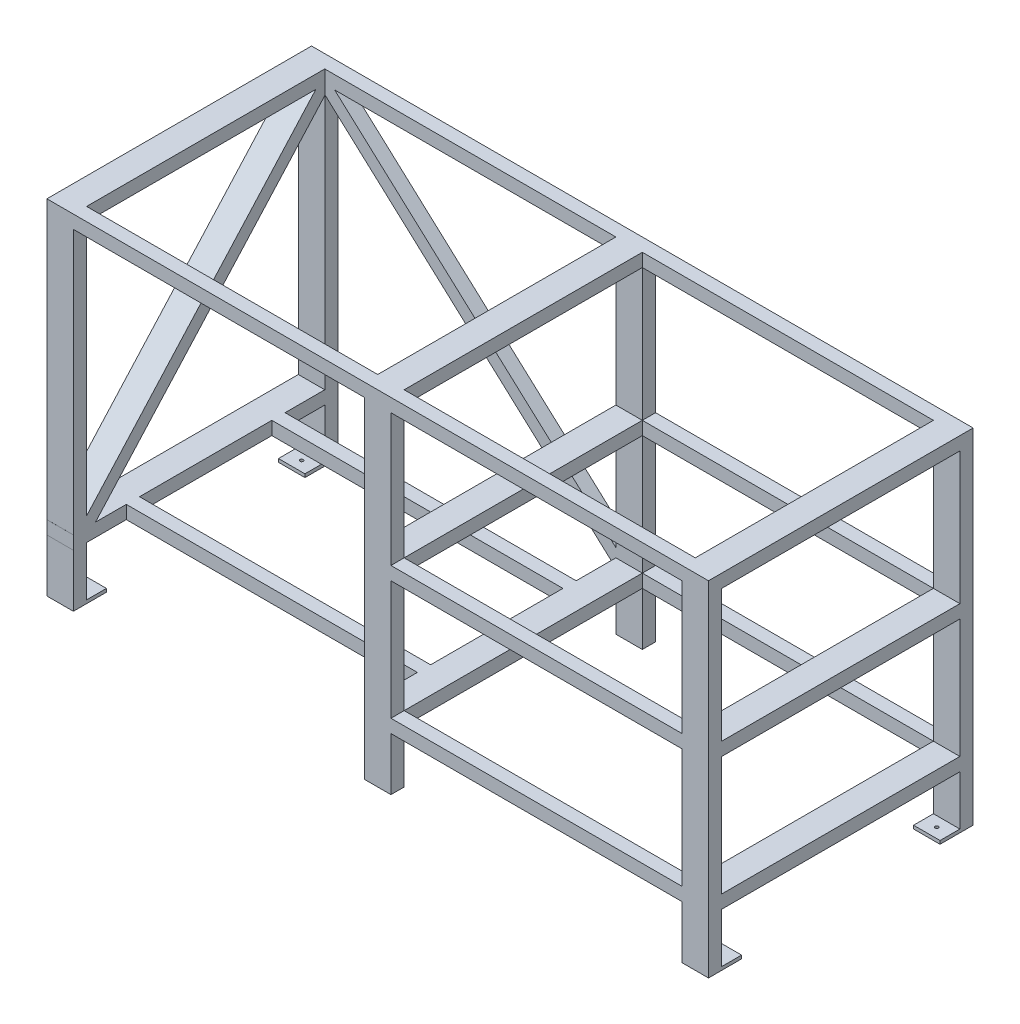
SolidWorks part; units mm, degrees
ref_plane "Front Plane" through (0, 0, 0) normal (0, 0, 1) x (1, 0, 0)
ref_plane "Top Plane" through (0, 0, 0) normal (0, 1, 0) x (1, 0, 0)
ref_plane "Right Plane" through (0, 0, 0) normal (1, 0, 0) x (0, 0, -1)
sketch "Sketch1" plane through (0, 0, 0) normal (0, 1, 0) x (1, 0, 0)
  line L0 (0, 0) -> (0, -232.9412) construction
  line L1 (-396.4706, 0) -> (-900, 0) construction
  line L2 (0, 360) -> (0, 400) construction
  line L3 (-1000, -360) -> (-920, -360)
  line L4 (-1000, -360) -> (-1000, -400)
  line L5 (-1000, -400) -> (-920, -400)
  line L6 (-920, -360) -> (-920, -400)
  line L7 (40, -360) -> (-40, -360)
  line L8 (0, -360) -> (0, -400) construction
  line L9 (40, -400) -> (-40, -400)
  line L10 (-40, -360) -> (-40, -400)
  line L11 (-40, 360) -> (-40, 400)
  line L12 (40, 400) -> (-40, 400)
  line L13 (40, 360) -> (-40, 360)
  line L14 (-920, 360) -> (-920, 400)
  line L15 (-1000, 400) -> (-920, 400)
  line L16 (-1000, 360) -> (-1000, 400)
  line L17 (-1000, 360) -> (-920, 360)
  line L18 (40, -360) -> (40, -400)
  line L19 (40, 360) -> (40, 400)
  line L20 (920, -360) -> (920, -400)
  line L21 (1000, -400) -> (920, -400)
  line L22 (1000, -360) -> (1000, -400)
  line L23 (1000, -360) -> (920, -360)
  line L24 (1000, 360) -> (920, 360)
  line L25 (1000, 360) -> (1000, 400)
  line L26 (1000, 400) -> (920, 400)
  line L27 (920, 360) -> (920, 400)
  dimension "D1" = 40
  dimension "D2" = 80
  dimension "D3" = 40
  dimension "D4" = 40
  dimension "D5" = 0
  dimension "D6" = 400
  dimension "D7" = 1000
  dimension "D8" = 0
  dimension "D9" = 400
extrude "Boss-Extrude1" add sketch "Sketch1" along normal blind 1000
ref_plane "Plane1" through (0, 200, 0) normal (0, -1, 0) x (-1, 0, 0)
sketch "Sketch3" plane through (0, 200, 0) normal (0, -1, 0) x (-1, 0, 0)
  line L0 (920, -240) -> (40, -240)
  line L1 (1000, 400) -> (920, 400)
  line L2 (1000, 400) -> (1000, -400.0751)
  line L3 (40, -400) -> (-1000, -400)
  line L4 (-1000, 400) -> (-1000, -400)
  line L5 (1000, -400) -> (920, -400) construction
  line L6 (920, 400) -> (920, 240)
  line L7 (40, 400) -> (-1000, 400)
  line L8 (40, 400) -> (40, 240)
  line L9 (-40, 360) -> (-920, 360)
  line L10 (-40, 360) -> (-40, -360)
  line L11 (-40, -360) -> (-920, -360)
  line L12 (-920, 360) -> (-920, -360)
  line L13 (920, -200) -> (40, -200)
  line L14 (920, 240) -> (40, 240)
  line L15 (920, 200) -> (40, 200)
  line L16 (1000, -400.0751) -> (920, -400.0751)
  line L17 (40, 200) -> (40, -200)
  line L18 (40, -240) -> (40, -400)
  line L19 (920, -240) -> (920, -400.0751)
  line L20 (920, 200) -> (920, -200)
  dimension "D1" = 200
  dimension "D2" = 40
  dimension "D3" = 200
  dimension "D4" = 40
extrude "Boss-Extrude2" add sketch "Sketch3" along normal blind 40
ref_plane "Plane3" through (0, 600, 0) normal (0, -1, 0) x (-1, 0, 0)
sketch "Sketch4" plane through (0, 600, 0) normal (0, -1, 0) x (-1, 0, 0)
  line L1 (40, 400) -> (-1000, 400)
  line L2 (40, 400) -> (40, -400)
  line L3 (40, -400) -> (-1000, -400)
  line L4 (-1000, 400) -> (-1000, -400)
  line L5 (-40, 360) -> (-920, 360)
  line L6 (-40, 360) -> (-40, -360)
  line L7 (-40, -360) -> (-920, -360)
  line L8 (-920, 360) -> (-920, -360)
extrude "Boss-Extrude4" add sketch "Sketch4" along normal blind 40
sketch "Sketch6" plane through (0, 1000, 0) normal (0, 1, 0) x (1, 0, 0)
  line L0 (40, -360) -> (-40, -360) construction
  line L1 (-1000, 400) -> (1000, 400)
  line L2 (-1000, 400) -> (-1000, -400)
  line L3 (-1000, -400) -> (1000, -400)
  line L4 (1000, 400) -> (1000, -400)
  line L5 (-920, 360) -> (-40, 360)
  line L6 (-920, 360) -> (-920, -360)
  line L7 (-920, -360) -> (-40, -360)
  line L8 (-40, 360) -> (-40, -360)
  line L10 (40, 360) -> (920, 360)
  line L11 (40, 360) -> (40, -360)
  line L12 (40, -360) -> (920, -360)
  line L13 (920, 360) -> (920, -360)
extrude "Boss-Extrude5" add sketch "Sketch6" along normal blind 40
sketch3d "3DSketch1"
  line L0 (-920, 200, 360) -> (-1000, 200, 360) construction
  line L1 (-960, 200, 360) -> (-960, 1000, -360)
  line L2 (-1000, 1000, -360) -> (-920, 1000, -360) construction
ref_plane "Plane4" through (-960, 200, 360) normal (0, 0.7433, -0.669) x (1, 0, 0)
sketch "Sketch7" plane through (-960, 200, 360) normal (0, 0.7433, -0.669) x (1, 0, 0)
  line L1 (-40, -20) -> (40, -20)
  line L2 (-40, -20) -> (-40, 20)
  line L3 (-40, 20) -> (40, 20)
  line L4 (40, -20) -> (40, 20)
  dimension "D1" = 20
  dimension "D2" = 40
  dimension "D3" = 40
  dimension "D4" = 80
sweep "Sweep1" add profiles "Sketch7" path "3DSketch1"
sketch3d "3DSketch2"
  line L0 (-40, 200, -380) -> (-920, 1000, -380)
  line L2 (-920, 1000, -360) -> (-920, 1000, -400) construction
ref_plane "Plane5" through (-40, 200, -380) normal (-0.7399, 0.6727, 0) x (0, 0, 1)
sketch "Sketch8" plane through (-40, 200, -380) normal (-0.7399, 0.6727, 0) x (0, 0, 1)
  line L1 (-20, 20) -> (20, 20)
  line L2 (-20, 20) -> (-20, -20)
  line L3 (-20, -20) -> (20, -20)
  line L4 (20, 20) -> (20, -20)
  dimension "D1" = 20
  dimension "D2" = 40
  dimension "D3" = 20
  dimension "D4" = 40
sweep "Sweep2" add profiles "Sketch8" path "3DSketch2"
sketch "Sketch9" plane through (0, 0, 0) normal (0, -1, 0) x (1, 0, 0)
  line L0 (1000, -400) -> (920, -400) construction
  line L1 (1000, -360) -> (920, -360)
  line L2 (1000, -360) -> (1000, -300)
  line L3 (1000, -300) -> (920, -300)
  line L4 (920, -360) -> (920, -300)
  circle A0 centre (960, -330) radius 5
  dimension "D2" = 10
  dimension "D1" = 100
  dimension "D3" = 40
  dimension "D4" = 30
extrude "Boss-Extrude6" add sketch "Sketch9" against normal blind 10 contours L2 L3 L4 L1
hole_wizard "Ø10.0 (10) Diameter Hole1" positions "Sketch11" profile "Sketch10" hole size "Ø10.0" standard "ANSI Metric"
sketch "Sketch11" plane through (0, 10, 0) normal (0, 1, 0) x (1, 0, 0)
  line L0 (1000, 300) -> (920, 300) construction
  point P0 (960, 330)
  dimension "D1" = 30
sketch "Sketch10" plane through (960, 10, -330) normal (1, 0, 0) x (0, 0, 1)
  line L0 (0, 0) -> (0, 10)
  line L1 (0, 10) -> (5, 10)
  line L2 (5, 10) -> (5, 0)
  line L5 (5, 0) -> (0, 0)
  line L11 (0, -6.35) -> (0, 107.95) construction
  dimension "Thru Hole Dia." = 10
  dimension "Thru Hole Depth" = 10
mirror "Mirror4" about plane through (0, 0, 0) normal (0, 0, 1) of "Boss-Extrude6", "Ø10.0 (10) Diameter Hole1"
mirror "Mirror5" about plane through (0, 0, 0) normal (1, 0, 0) of "Mirror4", "Boss-Extrude6", "Ø10.0 (10) Diameter Hole1"
